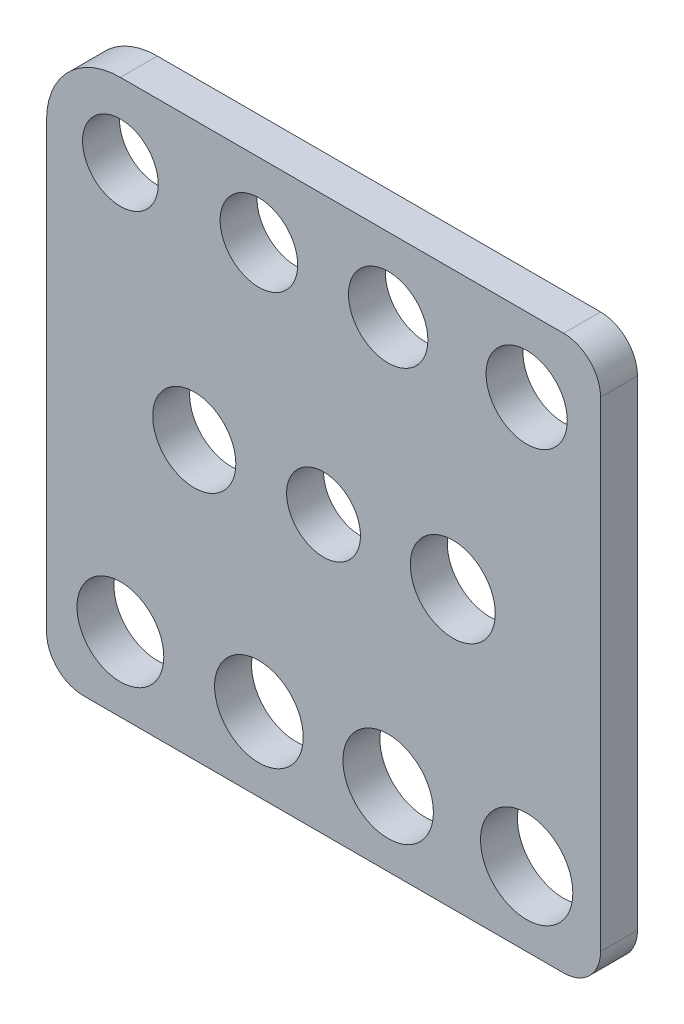
SolidWorks part; units mm, degrees
ref_plane "Alzado" through (0, 0, 0) normal (0, 0, 1) x (1, 0, 0)
ref_plane "Planta" through (0, 0, 0) normal (0, 1, 0) x (1, 0, 0)
ref_plane "Vista lateral" through (0, 0, 0) normal (1, 0, 0) x (0, 0, -1)
sketch "Croquis1" plane through (0, 0, 0) normal (0, 0, 1) x (1, 0, 0)
  line L1 (-84.9573, 47.7176) -> (-60.9573, 47.7176)
  line L2 (-88.9573, 43.7176) -> (-88.9573, 19.7176)
  line L3 (-86.9573, 17.7176) -> (-60.9573, 17.7176)
  line L4 (-58.9573, 45.7176) -> (-58.9573, 19.7176)
  circle A0 centre (-62.9573, 43.7176) radius 2.2
  circle A1 centre (-62.9573, 21.7176) radius 2.5
  circle A3 centre (-84.9573, 21.7176) radius 2.35
  circle A4 centre (-84.9573, 43.7176) radius 2.05
  circle A5 centre (-77.4573, 43.7215) radius 2.1
  circle A6 centre (-70.4573, 43.7221) radius 2.15
  circle A7 centre (-77.4573, 21.7215) radius 2.4
  circle A8 centre (-70.4573, 21.7221) radius 2.45
  circle A9 centre (-80.9573, 32.7176) radius 2.25
  circle A10 centre (-66.9573, 32.7176) radius 2.3
  circle A13 centre (-73.9573, 32.7176) radius 2
  arc A14 (-88.9573, 19.7176) -> (-86.9573, 17.7176) centre (-86.9573, 19.7176) ccw
  arc A15 (-60.9573, 17.7176) -> (-58.9573, 19.7176) centre (-60.9573, 19.7176) ccw
  arc A16 (-60.9573, 47.7176) -> (-58.9573, 45.7176) centre (-60.9573, 45.7176) cw
  arc A17 (-88.9573, 43.7176) -> (-84.9573, 47.7176) centre (-84.9573, 43.7176) cw
  point P4 (-81.2615, 32.7176)
  point P32 (-58.9573, 17.7176)
  point P35 (-58.9573, 47.7176)
  point P36 (-73.9573, 32.7176)
  dimension "D2" = 4.4
  dimension "D3" = 5
  dimension "D4" = 4.1
  dimension "D5" = 4.7
  dimension "D15" = 4.2
  dimension "D16" = 4.3
  dimension "D18" = 4.5
  dimension "D19" = 4.6
  dimension "D20" = 4.8
  dimension "D21" = 4.9
  dimension "D27" = 15
  dimension "D28" = 2
  dimension "D29" = 4
  dimension "D6" = 4
  dimension "D7" = 4
  dimension "D8" = 4
  dimension "D9" = 4
  dimension "D10" = 4
  dimension "D11" = 4
  dimension "D12" = 4
  dimension "D13" = 4
  dimension "D14" = 7.5
  dimension "D17" = 7.5
  dimension "D22" = 7.5
  dimension "D23" = 7.5
  dimension "D24" = 8
  dimension "D25" = 8
  dimension "D26" = 30
  dimension "D30" = 30
  dimension "D31" = 15
extrude "Saliente-Extruir1" add sketch "Croquis1" along normal blind 2
